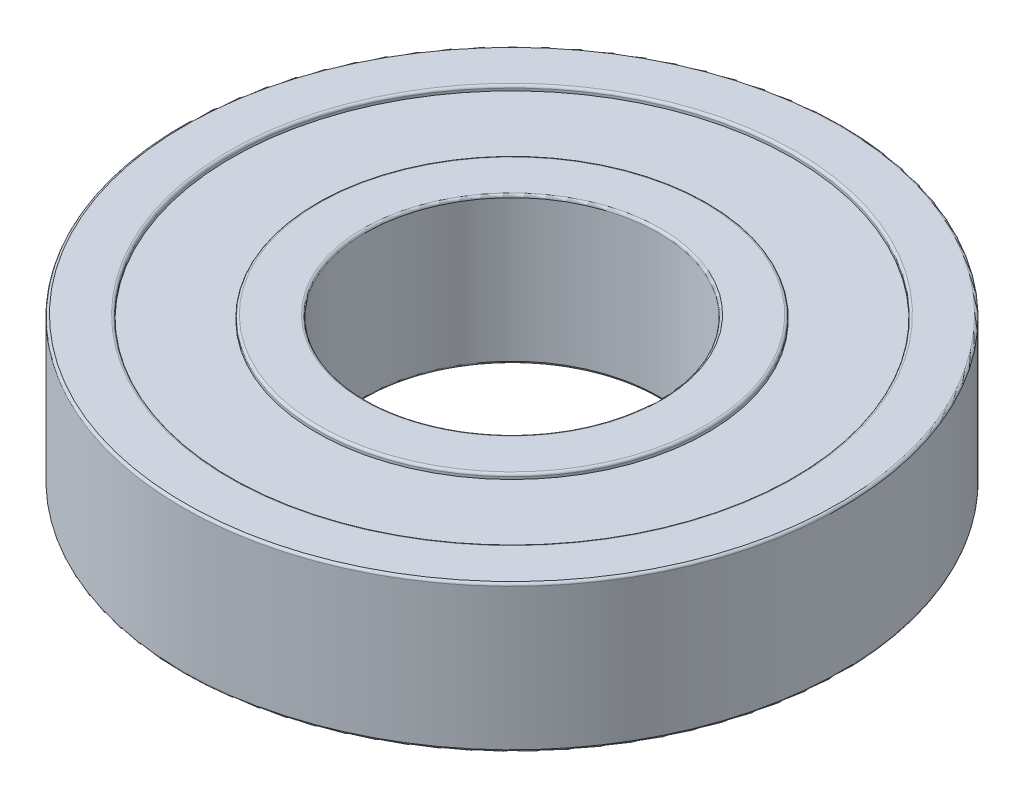
SolidWorks part; units mm, degrees
ref_plane "Front Plane" through (0, 0, 0) normal (0, 0, 1) x (1, 0, 0)
ref_plane "Top Plane" through (0, 0, 0) normal (0, 1, 0) x (1, 0, 0)
ref_plane "Right Plane" through (0, 0, 0) normal (1, 0, 0) x (0, 0, -1)
sketch "Sketch1" plane through (0, 0, 0) normal (0, 0, 1) x (1, 0, 0)
  line L0 (0, 0) -> (0, 11.7584) construction
  line L2 (-4.875, 0) -> (-4.875, 7.1092) construction
  line L3 (-6.75, 1.5) -> (-5.75, 1.5)
  line L4 (-5.75, 1.5) -> (-5.75, 0.85)
  line L5 (-6.75, 1.5) -> (-6.75, -1.5)
  line L6 (-6.75, -1.5) -> (-5.75, -1.5)
  line L7 (-5.75, -1.5) -> (-5.75, -0.85)
  line L8 (-4, -1.5) -> (-4, -0.85)
  line L9 (-3, -1.5) -> (-4, -1.5)
  line L10 (-3, 1.5) -> (-3, -1.5)
  line L11 (-3, 1.5) -> (-4, 1.5)
  line L12 (-4, 1.5) -> (-4, 0.85)
  arc A1 (-5.75, -0.85) -> (-5.75, 0.85) centre (-4.5141, 0) cw
  arc A2 (-4, -0.85) -> (-4, 0.85) centre (-5.2359, 0) ccw
  point P21 (-6.75, 0)
  dimension "D1" = 3
  dimension "D5" = 3
  dimension "D6" = 1.5
  dimension "D3" = 4.875
  dimension "D2" = 6.75
  dimension "D4" = 1
  dimension "D7" = 0.65
revolve "Revolve1" add sketch "Sketch1" angle 360 about L0
sketch "Sketch3" plane through (0, 0, 0) normal (0, 0, 1) x (1, 0, 0)
  line L0 (-5.75, 1.3) -> (-5.75, 1.4)
  line L1 (-5.75, 1.5) -> (-5.75, 0.85) construction
  line L2 (-5.75, 1.4) -> (-3, 1.4)
  line L3 (-3, 1.5) -> (-3, -1.5) construction
  line L4 (-3, 1.4) -> (-3, 1.3)
  line L5 (-3, 1.3) -> (-5.75, 1.3)
  line L7 (-4.875, 0) -> (-18.25, 0) construction
  line L8 (-3, -1.4) -> (-3, -1.3)
  line L9 (-3, -1.3) -> (-5.75, -1.3)
  line L10 (-5.75, -1.3) -> (-5.75, -1.4)
  line L11 (-5.75, -1.4) -> (-3, -1.4)
  dimension "D1" = 1.3
  dimension "D2" = 0.1
revolve "Revolve3" add sketch "Sketch3" angle 360 about L0
fillet "Fillet1" radius 0.05 4 edges at (0, -1.5, -6.75) (0, -1.5, -5.75) (0, 1.5, -5.75) (0, 1.5, -6.75)
fillet "Fillet2" radius 0.05 4 edges at (0, -1.5, -4) (0, -1.5, -3) (0, 1.5, -3) (0, 1.5, -4)
